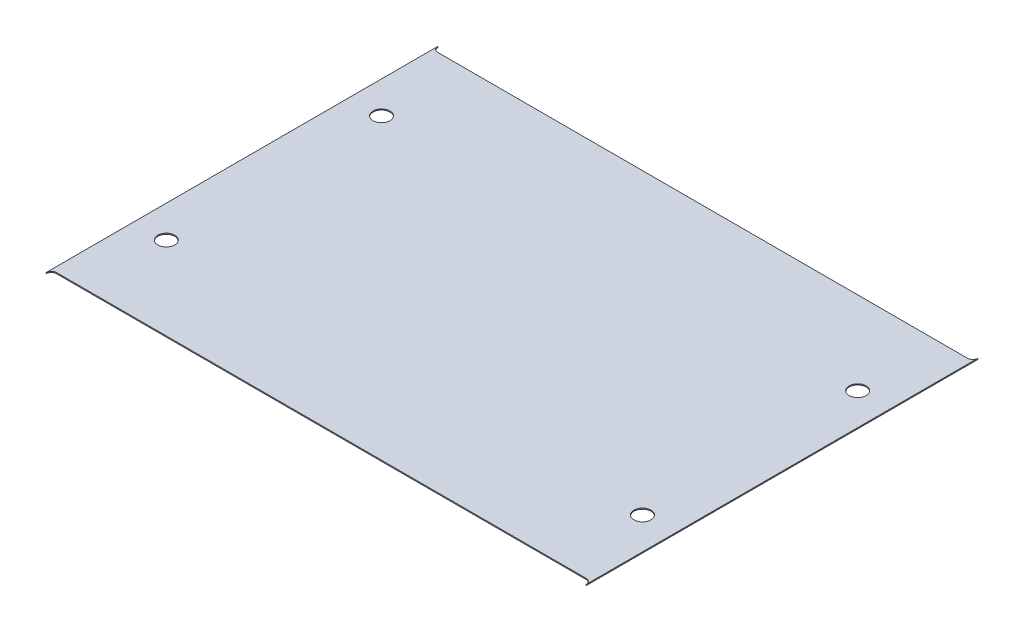
SolidWorks part; units mm, degrees
ref_plane "Front Plane" through (0, 0, 0) normal (0, 0, 1) x (1, 0, 0)
ref_plane "Top Plane" through (0, 0, 0) normal (0, 1, 0) x (1, 0, 0)
ref_plane "Right Plane" through (0, 0, 0) normal (1, 0, 0) x (0, 0, -1)
sketch "Sketch2" plane through (0, 0, 0) normal (0, 1, 0) x (1, 0, 0)
  line L4 (-49.9289, 21.9313) -> (-49.9289, -15.0687)
  line L5 (-49.4289, -14.5687) -> (0.5711, -14.5687)
  line L6 (-49.9289, 21.9313) -> (-49.9289, -15.0687)
  line L7 (0.5711, 21.4313) -> (-49.4289, 21.4313)
  line L9 (-49.4289, -14.5687) -> (0.5711, -14.5687)
  line L11 (0.5711, 21.4313) -> (-49.4289, 21.4313)
  line L20 (1.0711, -15.0687) -> (1.0711, 21.9313)
  line L21 (1.0711, -15.0687) -> (1.0711, 21.9313)
  arc A12 (1.0711, -15.0687) -> (0.5711, -14.5687) centre (0.5711, -15.0687) ccw
  arc A13 (1.0711, -15.0687) -> (0.5711, -14.5687) centre (0.5711, -15.0687) ccw
  arc A14 (-49.4289, -14.5687) -> (-49.9289, -15.0687) centre (-49.4289, -15.0687) ccw
  arc A15 (-49.4289, -14.5687) -> (-49.9289, -15.0687) centre (-49.4289, -15.0687) ccw
  arc A16 (-49.9289, 21.9313) -> (-49.4289, 21.4313) centre (-49.4289, 21.9313) ccw
  arc A17 (-49.9289, 21.9313) -> (-49.4289, 21.4313) centre (-49.4289, 21.9313) ccw
  arc A18 (0.5711, 21.4313) -> (1.0711, 21.9313) centre (0.5711, 21.9313) ccw
  arc A19 (0.5711, 21.4313) -> (1.0711, 21.9313) centre (0.5711, 21.9313) ccw
  circle A20 centre (-1.9489, 13.5913) radius 0.8 construction
  circle A21 centre (-46.9089, 13.5913) radius 0.8 construction
  circle A22 centre (-46.9089, -6.7287) radius 0.8 construction
  circle A23 centre (-1.9489, -6.7287) radius 0.8 construction
  circle A24 centre (-1.9489, 13.5913) radius 0.8
  circle A25 centre (-46.9089, 13.5913) radius 0.8
  circle A26 centre (-46.9089, -6.7287) radius 0.8
  circle A27 centre (-1.9489, -6.7287) radius 0.8
  dimension "D1" = 0
extrude "Boss-Extrude2" add sketch "Sketch2" along normal blind 0.1
